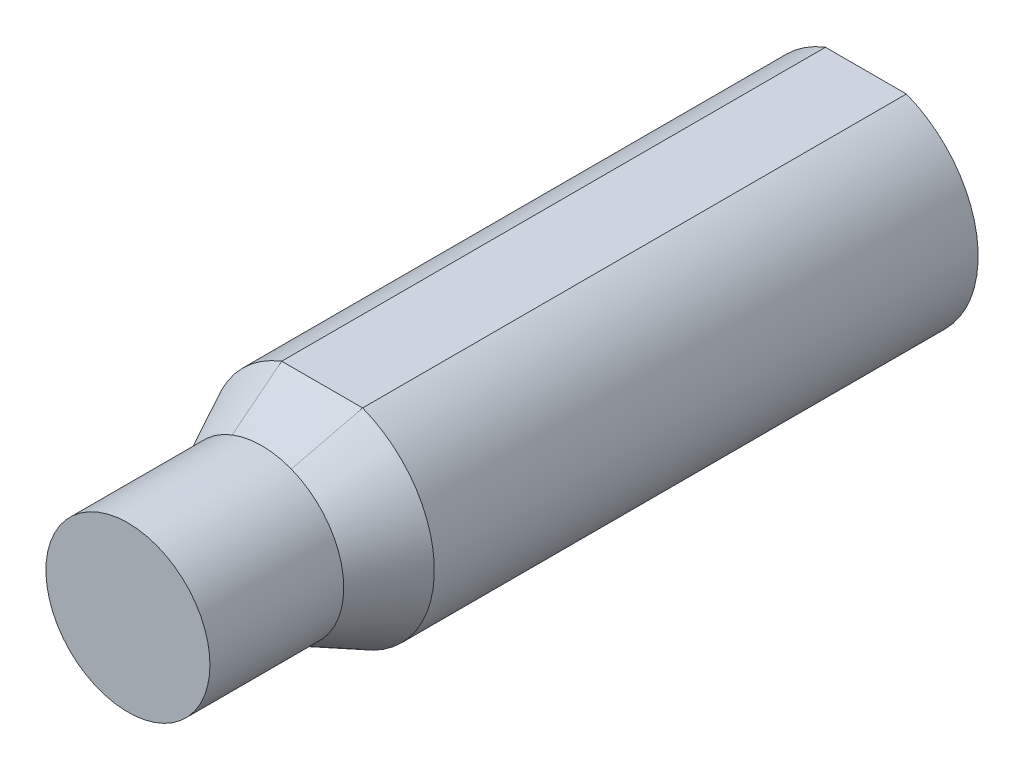
SolidWorks part; units mm, degrees
ref_plane "Front Plane" through (0, 0, 0) normal (0, 0, 1) x (1, 0, 0)
ref_plane "Top Plane" through (0, 0, 0) normal (0, 1, 0) x (1, 0, 0)
ref_plane "Right Plane" through (0, 0, 0) normal (1, 0, 0) x (0, 0, -1)
sketch "Sketch1" plane through (0, 0, 0) normal (0, 0, 1) x (1, 0, 0)
  line L0 (-0.9377, 2.425) -> (0.9377, 2.425)
  line L1 (-0.9377, -2.425) -> (0.9377, -2.425)
  line L2 (0, 0) -> (0, 2.425) construction
  line L3 (0, 0) -> (0, -2.425) construction
  arc A0 (-0.9377, 2.425) -> (-0.9377, -2.425) centre (0, 0) ccw
  arc A1 (0.9377, -2.425) -> (0.9377, 2.425) centre (0, 0) ccw
  dimension "D1" = 5.2
  dimension "D2" = 4.85
extrude "Boss-Extrude1" add sketch "Sketch1" along normal blind 12.6
ref_plane "Plane1" through (0, 0, 14) normal (0, 0, 1) x (1, 0, 0)
sketch "Sketch2" plane through (0, 0, 14) normal (0, 0, 1) x (1, 0, 0)
  circle A0 centre (0, 0) radius 1.9
  dimension "D1" = 3.8
sketch "Sketch3" plane through (0, 0, 12.6) normal (0, 0, 1) x (1, 0, 0)
  line L2 (-0.9377, -2.425) -> (0.9377, -2.425)
  line L3 (0.9377, 2.425) -> (-0.9377, 2.425)
  line L4 (-0.9377, -2.425) -> (0.9377, -2.425)
  line L5 (0.9377, 2.425) -> (-0.9377, 2.425)
  arc A2 (-0.9377, 2.425) -> (-0.9377, -2.425) centre (0, 0) ccw
  arc A3 (0.9377, -2.425) -> (0.9377, 2.425) centre (0, 0) ccw
  arc A4 (-0.9377, 2.425) -> (-0.9377, -2.425) centre (0, 0) ccw
  arc A5 (0.9377, -2.425) -> (0.9377, 2.425) centre (0, 0) ccw
  dimension "D1" = 0
loft "Loft1" add profiles "Sketch2", "Sketch3"
sketch "Sketch4" plane through (0, 0, 14) normal (0, 0, 1) x (1, 0, 0)
  arc A4 (0.6853, 1.7721) -> (-0.6853, 1.7721) centre (0, 0) ccw
  arc A5 (-0.6853, 1.7721) -> (-0.6853, -1.7721) centre (0, 0) ccw
  arc A6 (-0.6853, -1.7721) -> (0.6853, -1.7721) centre (0, 0) ccw
  arc A7 (0.6853, -1.7721) -> (0.6853, 1.7721) centre (0, 0) ccw
  arc A8 (0.6853, 1.7721) -> (-0.6853, 1.7721) centre (0, 0) ccw
  arc A9 (-0.6853, 1.7721) -> (-0.6853, -1.7721) centre (0, 0) ccw
  arc A10 (-0.6853, -1.7721) -> (0.6853, -1.7721) centre (0, 0) ccw
  arc A11 (0.6853, -1.7721) -> (0.6853, 1.7721) centre (0, 0) ccw
  dimension "D1" = 0
extrude "Boss-Extrude2" add sketch "Sketch4" along normal blind 3.1
